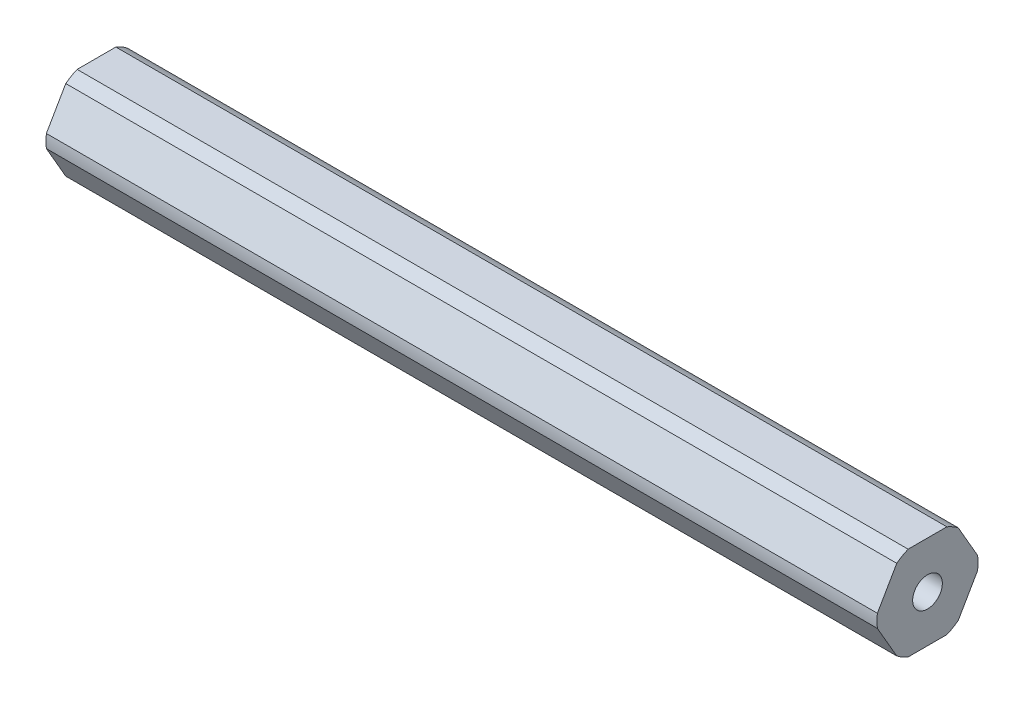
SolidWorks part; units mm, degrees
material "6061-T6 (SS)"
ref_plane "Front Plane" through (0, 0, 0) normal (0, 0, 1) x (1, 0, 0)
ref_plane "Top Plane" through (0, 0, 0) normal (0, 1, 0) x (1, 0, 0)
ref_plane "Right Plane" through (0, 0, 0) normal (1, 0, 0) x (0, 0, -1)
sketch "Sketch1" plane through (0, 0, 0) normal (1, 0, 0) x (0, 0, -1)
  line L1 (7.3323, 0) -> (3.6662, 6.35)
  line L2 (3.6662, 6.35) -> (-3.6662, 6.35)
  line L3 (-3.6662, 6.35) -> (-7.3323, 0)
  line L4 (-7.3323, 0) -> (-3.6662, -6.35)
  line L5 (-3.6662, -6.35) -> (3.6662, -6.35)
  line L6 (3.6662, -6.35) -> (7.3323, 0)
  circle A0 centre (0, 0) radius 6.35 construction
  circle A1 centre (0, 0) radius 6.875
  circle A2 centre (0, 0) radius 2.0193
  dimension "D1" = 12.7
  dimension "D2" = 13.75
  dimension "D3" = 4.0386
extrude "Boss-Extrude1" add sketch "Sketch1" along normal mid plane 113.03 contours L1 A1 L2 L3 L4 L5 L6 A2
equation "\"D2@Sketch1\"=13.75MM"
equation "\"D3@Sketch1\"=.159"
